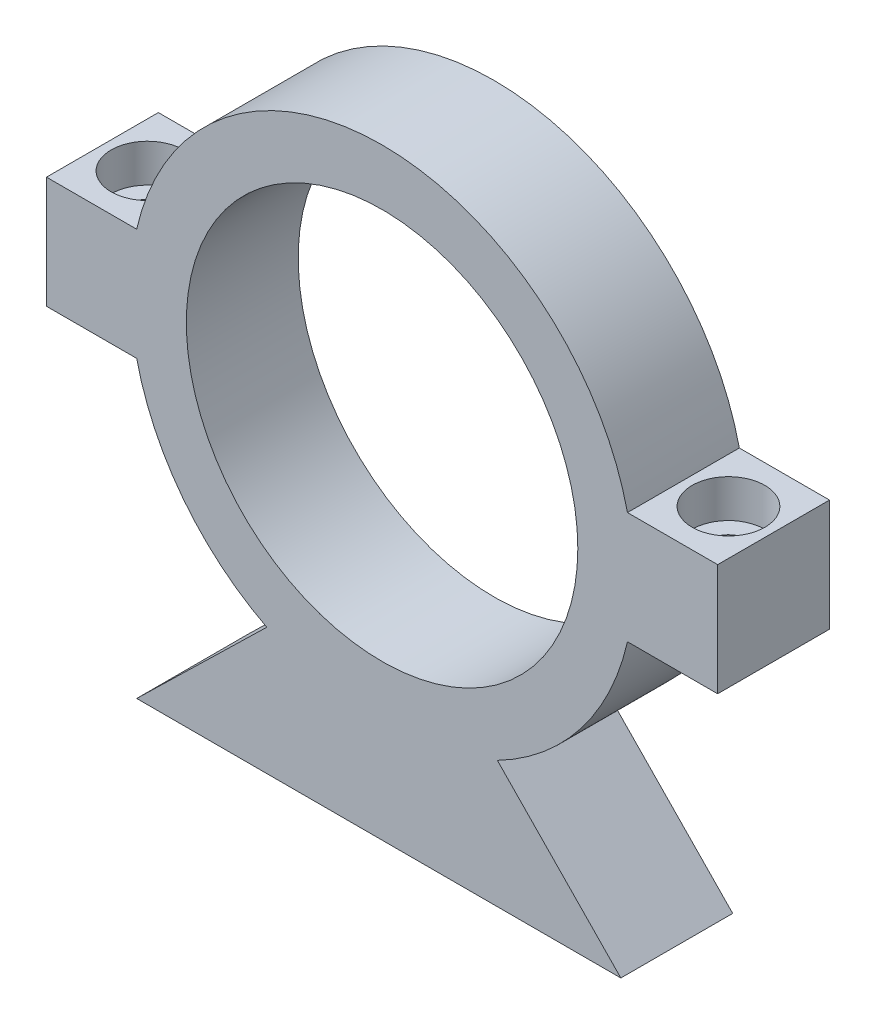
SolidWorks part; units mm, degrees
ref_plane "Plan de face" through (0, 0, 0) normal (0, 0, 1) x (1, 0, 0)
ref_plane "Plan de dessus" through (0, 0, 0) normal (0, 1, 0) x (1, 0, 0)
ref_plane "Plan de droite" through (0, 0, 0) normal (1, 0, 0) x (0, 0, -1)
sketch "Esquisse1" plane through (0, 0, 0) normal (0, 0, 1) x (1, 0, 0)
  line L0 (-67.7525, 0) -> (40.8062, 0) construction
  line L1 (0, 31.7939) -> (0, -33.5368) construction
  line L2 (30, -5) -> (30, 5)
  line L3 (30, 5) -> (21.9374, 5)
  line L4 (-30, 5) -> (-21.9374, 5)
  line L5 (-30, -5) -> (-30, 5)
  line L6 (30, -5) -> (21.9374, -5)
  line L7 (-30, -5) -> (-21.9374, -5)
  line L9 (-10.3078, -20) -> (-21.9374, -31.33)
  line L10 (-21.9374, -31.33) -> (21.3458, -31.33)
  line L11 (21.3458, -31.33) -> (10.3078, -20)
  circle A0 centre (0, 0) radius 17.5
  arc A1 (21.9374, 5) -> (-21.9374, 5) centre (0, 0) ccw
  arc A2 (21.9374, -5) -> (10.3078, -20) centre (0, 0) cw
  arc A3 (-10.3078, -20) -> (-21.9374, -5) centre (0, 0) cw
  point P19 (30, 0)
  point P22 (-30, 0)
  dimension "D1" = 35
  dimension "D3" = 5
  dimension "D5" = 20
  dimension "D2" = 30
  dimension "D4" = 5
  dimension "D6" = 11.33
  dimension "D7" = 43.2832
  dimension "D8" = 31.33
extrude "Boss.-Extru.1" add sketch "Esquisse1" along normal blind 10
sketch "Esquisse2" plane through (0, 5, 0) normal (0, 1, 0) x (1, 0, 0)
  line L0 (30, 0) -> (21.9374, 0) construction
  line L1 (30, -10) -> (30, 0) construction
  circle A0 centre (25.97, -5) radius 2
  point P6 (30, -5)
  dimension "D3" = 4
  dimension "D1" = 5
  dimension "D2" = 4.03
hole_wizard "Chambrage pour vis à tête hexagonale M31" positions "Esquisse3D1" profile "Esquisse3" counterbore size "M3" standard "ISO" end condition through all
sketch3d "Esquisse3D1"
  point P0 (25.97, 5, 5)
sketch "Esquisse3" plane through (25.97, 5, 5) normal (1, 0, 0) x (0, 0, 1)
  line L0 (0, 0) -> (0, 36.33)
  line L1 (0, 36.33) -> (1.7, 36.33)
  line L3 (1.7, 36.33) -> (1.7, 3.4)
  line L4 (1.7, 3.4) -> (3.25, 3.4)
  line L5 (3.25, 3.4) -> (3.25, 0)
  line L7 (3.25, 0) -> (0, 0)
  line L11 (0, -6.35) -> (0, 107.95) construction
  dimension "Diamètre du perçage jusqu'au prochain" = 3.4
  dimension "Profondeur du perçage jusqu'au prochain" = 36.33
  dimension "Diamètre du chambrage" = 6.5
  dimension "Profondeur du chambrage" = 3.4
mirror "Symétrie2" about plane through (0, 0, 0) normal (1, 0, 0) of "Chambrage pour vis à tête hexagonale M31"
